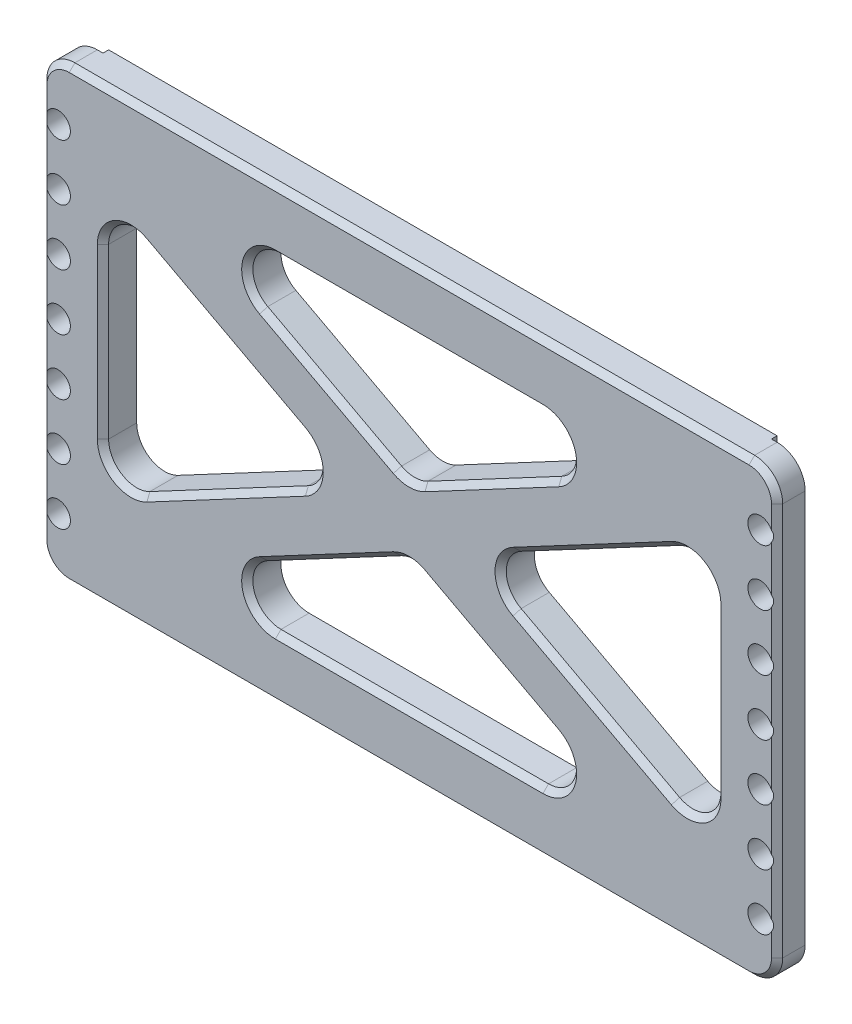
SolidWorks part; units mm, degrees
material "7075-T6 (SN)"
ref_plane "前视基准面" through (0, 0, 0) normal (0, 0, 1) x (1, 0, 0)
ref_plane "上视基准面" through (0, 0, 0) normal (0, 1, 0) x (1, 0, 0)
ref_plane "右视基准面" through (0, 0, 0) normal (1, 0, 0) x (0, 0, -1)
sketch "草图3" plane through (0, 0, 0) normal (0, 0, 1) x (1, 0, 0)
  line L0 (-57.5, -11.5) -> (57.5, -11.5) construction
  line L1 (-65.5, -11.5) -> (65.5, -11.5)
  line L2 (-65.5, -91.5) -> (65.5, -91.5)
  line L3 (65.5, -5.5) -> (65.5, -101.8916) construction
  line L4 (-65.5, -101.8916) -> (-65.5, -5.5) construction
  line L5 (65.5, -11.5) -> (65.5, -91.5)
  line L6 (-65.5, -91.5) -> (-65.5, -11.5)
  line L7 (-57.5, -11.5) -> (57.5, -11.5) construction
  line L8 (-57.5, -91.5) -> (57.5, -91.5) construction
  dimension "D1" = 80
extrude "凸台-拉伸3" add sketch "草图3" along normal blind 5
sketch "草图4" plane through (0, 0, 5) normal (0, 0, 1) x (1, 0, 0)
  line L0 (-65.5, -91.5) -> (65.5, -91.5) construction
  line L1 (59.5, -91.5) -> (-59.5, -91.5)
  line L2 (59.5, -91.5) -> (59.5, -11.5)
  line L3 (59.5, -11.5) -> (-59.5, -11.5)
  line L4 (-59.5, -91.5) -> (-59.5, -11.5)
  line L5 (59.5, -11.5) -> (59.5, -101.8916) construction
  line L6 (60.5, -11.5) -> (-60.5, -11.5) construction
  line L7 (65.5, -11.5) -> (-65.5, -11.5) construction
extrude "凸台-拉伸4" add sketch "草图4" against normal blind 6
fillet "圆角2" radius 5 4 edges at (65.5, -11.5, 2.5) (-65.5, -11.5, 2.5) (-65.5, -91.5, 2.5) (65.5, -91.5, 2.5)
chamfer "倒角1" distance 1 angle 45 8 edges at (-65.5, -51.5, 5) (-64.0355, -90.0355, 5) (-64.0355, -12.9645, 5) (0, -91.5, 5) (0, -11.5, 5) (64.0355, -90.0355, 5) (64.0355, -12.9645, 5) (65.5, -51.5, 5)
sketch "草图5" plane through (0, 0, 5) normal (0, 0, 1) x (1, 0, 0)
  line L4 (-54.5, -22.5) -> (54.5, -80.5)
  line L5 (-54.5, -80.5) -> (54.5, -22.5)
  line L6 (-52.1513, -84.914) -> (56.8487, -26.914)
  line L7 (-56.8487, -26.914) -> (52.1513, -84.914)
  line L8 (-54.5, -22.5) -> (-54.5, -80.5)
  line L9 (-54.5, -80.5) -> (54.5, -80.5)
  line L10 (54.5, -80.5) -> (54.5, -22.5)
  line L11 (54.5, -22.5) -> (-54.5, -22.5)
  line L12 (-54.5, -22.5) -> (-54.5, -80.5)
  line L13 (-54.5, -80.5) -> (54.5, -80.5)
  line L14 (54.5, -80.5) -> (54.5, -22.5)
  line L15 (54.5, -22.5) -> (-54.5, -22.5)
  line L16 (-56.8487, -76.086) -> (52.1513, -18.086)
  line L17 (-52.1513, -18.086) -> (56.8487, -76.086)
  dimension "D2" = 5
  dimension "D1" = 10
  dimension "D3" = 5
extrude "切除-拉伸1" cut sketch "草图5" against normal blind 6 contours L12 L16 L7 | L15 L17 L16 | L6 L17 L14 | L6 L13 L7
fillet "圆角3" radius 5 12 edges at (54.5, -28.1638, 2) (54.5, -74.8362, 2) (10.644, -51.5, 2) (0, -45.8362, 2) (-43.856, -22.5, 2) (43.856, -22.5, 2) (-10.644, -51.5, 2) (-54.5, -74.8362, 2) (-54.5, -28.1638, 2) (0, -57.1638, 2) (43.856, -80.5, 2) (-43.856, -80.5, 2)
chamfer "倒角2" distance 1 angle 45 24 edges at (-52.0745, -70.7981, 5) (-54.5, -51.5, 5) (-33.0453, -63.4199, 5) (-52.0745, -32.2019, 5) (-16.288, -51.5, 5) (-33.0453, -39.5801, 5) (28.6667, -26.2896, 5) (0, -22.5, 5) (14.2564, -38.2502, 5) (-28.6667, -26.2896, 5) (0, -45.1724, 5) (-14.2564, -38.2502, 5) (52.0745, -32.2019, 5) (33.0453, -39.5801, 5) (54.5, -51.5, 5) (16.288, -51.5, 5) (52.0745, -70.7981, 5) (33.0453, -63.4199, 5) (-28.6667, -76.7104, 5) (-14.2564, -64.7498, 5) (0, -80.5, 5) (0, -57.8276, 5) (28.6667, -76.7104, 5) (14.2564, -64.7498, 5)
sketch "草图6" plane through (0, 0, 5) normal (0, 0, 1) x (1, 0, 0)
  line L0 (65.5, -51.5) -> (59.5, -51.5) construction
  line L1 (65.5, -16.5) -> (65.5, -86.5) construction
  line L2 (62.5, -41.5) -> (62.5, -61.5) construction
  line L3 (62.5, -31.5) -> (62.5, -71.5) construction
  line L4 (62.5, -21.5) -> (62.5, -81.5) construction
  circle A0 centre (62.5, -21.5) radius 2.2
  circle A1 centre (62.5, -31.5) radius 2.2
  circle A2 centre (62.5, -41.5) radius 2.2
  circle A3 centre (62.5, -51.5) radius 2.2
  circle A4 centre (62.5, -61.5) radius 2.2
  circle A5 centre (62.5, -71.5) radius 2.2
  circle A6 centre (62.5, -81.5) radius 2.2
  point P7 (62.5, -51.5)
  point P11 (62.5, -51.5)
  point P14 (62.5, -51.5)
  dimension "D1" = 7
extrude "切除-拉伸2" cut sketch "草图6" against normal blind 11
mirror "镜向1" about plane through (0, 0, 0) normal (1, 0, 0) of "切除-拉伸2"
